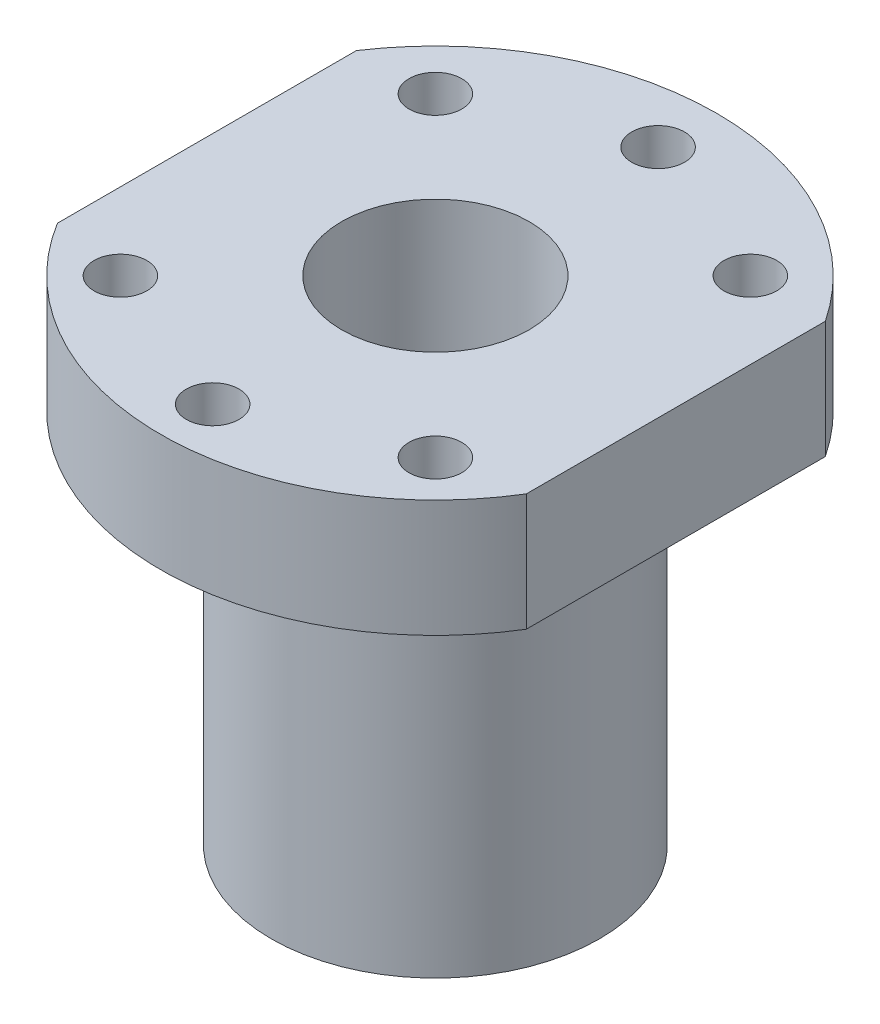
SolidWorks part; units mm, degrees
ref_plane "前视" through (0, 0, 0) normal (0, 0, 1) x (1, 0, 0)
ref_plane "上视" through (0, 0, 0) normal (0, 1, 0) x (1, 0, 0)
ref_plane "右视" through (0, 0, 0) normal (1, 0, 0) x (0, 0, -1)
sketch "Sketch1" plane through (0, 0, 0) normal (0, 1, 0) x (1, 0, 0)
  line L0 (-121.9967, -1.865) -> (-81.9967, -1.865) construction
  line L1 (-101.9967, -1.865) -> (-101.9967, 23.6864) construction
  line L2 (-81.9967, 11.4015) -> (-81.9967, -14.1055)
  line L3 (-121.9967, 11.4015) -> (-121.9967, -14.1055)
  arc A0 (-81.9967, 11.4015) -> (-121.9967, 11.4015) centre (-101.9967, -1.865) ccw
  arc A1 (-81.9967, -14.1055) -> (-121.9967, -14.1055) centre (-101.9967, -1.865) cw
  circle A2 centre (-101.9967, -1.865) radius 8
  circle A4 centre (-101.9967, 17.135) radius 2.25
  circle A5 centre (-88.5617, 11.57) radius 2.25
  circle A6 centre (-115.4317, 11.57) radius 2.25
  circle A7 centre (-101.9967, -20.865) radius 2.25
  circle A8 centre (-88.5617, -15.3001) radius 2.25
  circle A9 centre (-115.4317, -15.3001) radius 2.25
  point P18 (-101.9967, -1.865)
  point P26 (-101.9967, -1.865)
  dimension "D2" = 2
  dimension "D1" = 40
  dimension "D3" = 2
extrude "Extrude1" add sketch "Sketch1" along normal blind 10
sketch "Sketch2" plane through (0, 0, 0) normal (0, -1, 0) x (1, 0, 0)
  circle A0 centre (-101.9967, 1.865) radius 14
  circle A1 centre (-101.9967, 1.865) radius 8
extrude "Extrude2" add sketch "Sketch2" along normal blind 32
